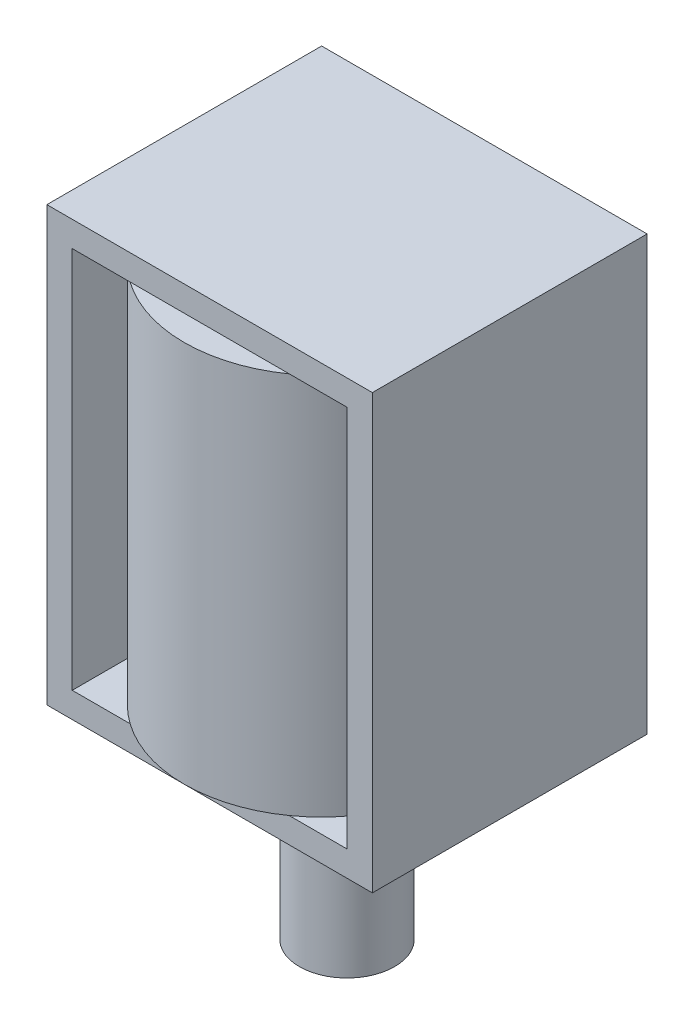
SolidWorks part; units mm, degrees
ref_plane "Plan de face" through (0, 0, 0) normal (0, 0, 1) x (1, 0, 0)
ref_plane "Plan de dessus" through (0, 0, 0) normal (0, 1, 0) x (1, 0, 0)
ref_plane "Plan de droite" through (0, 0, 0) normal (1, 0, 0) x (0, 0, -1)
sketch "Esquisse1" plane through (0, 0, 0) normal (0, 0, 1) x (1, 0, 0)
  line L0 (-6.5, 1.2) -> (6.5, 1.2)
  line L1 (-7.7, 0) -> (7.7, 0)
  line L2 (-7.7, 0) -> (-7.7, 20.5)
  line L3 (-7.7, 20.5) -> (7.7, 20.5)
  line L4 (7.7, 0) -> (7.7, 20.5)
  line L5 (6.5, 1.2) -> (6.5, 19.3)
  line L6 (-6.5, 19.3) -> (6.5, 19.3)
  line L7 (-6.5, 1.2) -> (-6.5, 19.3)
  dimension "D1" = 20.5
  dimension "D2" = 15.4
  dimension "D3" = 1.2
extrude "Boss.-Extru.1" add sketch "Esquisse1" along normal mid plane 13
sketch "Esquisse2" plane through (0, 0, 0) normal (0, -1, 0) x (1, 0, 0)
  circle A0 centre (0, 0) radius 2.25
  dimension "D1" = 4.5
extrude "Boss.-Extru.2" add sketch "Esquisse2" along normal blind 9
sketch "Esquisse3" plane through (0, 1.2, 0) normal (0, 1, 0) x (1, 0, 0)
  line L0 (0, 0) -> (0, -1.2) construction
  line L1 (6.5, 0) -> (6.5, -1.2)
  line L2 (-6.5, 0) -> (-6.5, -1.2)
  line L3 (-6.5, 6.5) -> (6.5, 6.5) construction
  arc A0 (6.5, 0) -> (-6.5, 0) centre (0, 0) ccw
  arc A1 (-6.5, -1.2) -> (6.5, -1.2) centre (0, -1.2) ccw
  point P3 (0, -0.6)
  dimension "D1" = 1.2
extrude "Boss.-Extru.3" add sketch "Esquisse3" along normal up to surface (18.1 mm away) up to face at (0, 19.3, 0)
